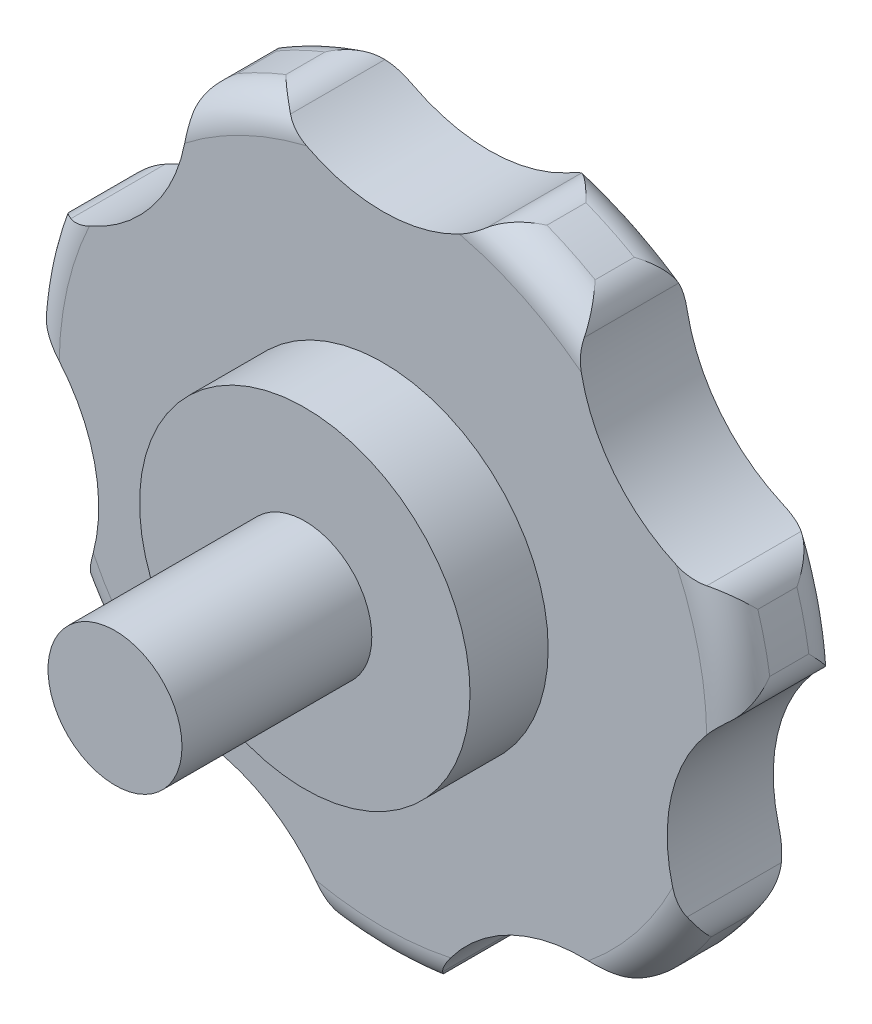
SolidWorks part; units mm, degrees
ref_plane "Front Plane" through (0, 0, 0) normal (0, 0, 1) x (1, 0, 0)
ref_plane "Top Plane" through (0, 0, 0) normal (0, 1, 0) x (1, 0, 0)
ref_plane "Right Plane" through (0, 0, 0) normal (1, 0, 0) x (0, 0, -1)
sketch "Sketch1" plane through (0, 0, 0) normal (0, 0, 1) x (1, 0, 0)
  circle A0 centre (0, 0) radius 16
  dimension "D1" = 32
extrude "Boss-Extrude1" add sketch "Sketch1" along normal blind 8.5
sketch "Sketch2" plane through (0, 0, 8.5) normal (0, 0, 1) x (1, 0, 0)
  circle A0 centre (0, 0) radius 7.4
  dimension "D1" = 14.8
extrude "Boss-Extrude2" add sketch "Sketch2" along normal blind 3.5
sketch "Sketch3" plane through (0, 0, 12) normal (0, 0, 1) x (1, 0, 0)
  circle A0 centre (0, 0) radius 3
  dimension "D1" = 6
extrude "Cut-Extrude1" cut sketch "Sketch3" against normal blind 3.5
sketch "Sketch4" plane through (0, 0, 0) normal (0, 1, 0) x (1, 0, 0)
  line L0 (-16, -3.75) -> (16, -3.75) construction
  line L1 (-16, 0) -> (-16, -8.5) construction
  line L2 (16, -8.5) -> (16, 0) construction
  line L3 (-8.5, 0) -> (-8.5, -8.5) construction
  line L4 (16, 0) -> (-16, 0) construction
  line L5 (-16, -8.5) -> (16, -8.5) construction
  line L6 (11, 0) -> (11, -8.5) construction
  line L7 (0, 0) -> (0, 2.9223)
  line L8 (0, 2.9223) -> (-18.6037, 2.9223)
  line L9 (-18.6037, 2.9223) -> (-18.6037, -3.75)
  line L10 (-18.6037, -3.75) -> (-8.5, -3.75)
  arc A0 (-8.5, -3.75) -> (0, 0) centre (0, -11.5083) cw
  point P16 (0, 0)
  dimension "D1" = 7.5
  dimension "D2" = 5
  dimension "D3" = 3.75
revolve "Cut-Revolve1" cut sketch "Sketch4" angle 360 about L7
sketch "Sketch5" plane through (0, 0, 3.75) normal (0, 0, -1) x (-1, 0, 0)
  arc A0 (-5, 15.1987) -> (5, 15.1987) centre (0, 20.6255) ccw
  circle A1 centre (0, 0) radius 16 construction
  arc A2 (8.7654, 13.3854) -> (15.0003, 5.5671) centre (16.1256, 12.8598) ccw
  arc A3 (15.9302, 1.4926) -> (13.705, -8.2567) centre (20.1083, -4.5896) ccw
  arc A4 (11.0993, -11.5241) -> (2.0896, -15.863) centre (8.9491, -18.5829) ccw
  arc A5 (-2.0896, -15.863) -> (-11.0993, -11.5241) centre (-8.9491, -18.5829) ccw
  arc A6 (-13.705, -8.2567) -> (-15.9302, 1.4926) centre (-20.1083, -4.5896) ccw
  arc A7 (-15.0003, 5.5671) -> (-8.7654, 13.3854) centre (-16.1256, 12.8598) ccw
  arc A8 (-15.0003, 5.5671) -> (-15.9302, 1.4926) centre (0, 0) ccw
  arc A9 (-5, 15.1987) -> (-8.7654, 13.3854) centre (0, 0) ccw
  arc A10 (8.7654, 13.3854) -> (5, 15.1987) centre (0, 0) ccw
  arc A11 (15.9302, 1.4926) -> (15.0003, 5.5671) centre (0, 0) ccw
  arc A12 (11.0993, -11.5241) -> (13.705, -8.2567) centre (0, 0) ccw
  arc A13 (-2.0896, -15.863) -> (2.0896, -15.863) centre (0, 0) ccw
  arc A14 (-13.705, -8.2567) -> (-11.0993, -11.5241) centre (0, 0) ccw
  circle A15 centre (0, 0) radius 17.9062
  point P28 (0, 0)
  dimension "D1" = 5
  dimension "D2" = 5
  dimension "D3" = 7
extrude "Cut-Extrude2" cut sketch "Sketch5" against normal through all
fillet "Fillet1" radius 1.5 28 edges at (12.5093, -9.9758, 8.5) (13.705, -8.2567, 6.125) (15.9302, 1.4926, 6.125) (12.5093, -9.9758, 3.75) (2.0896, -15.863, 6.125) (11.0993, -11.5241, 6.125) (15.5988, 3.5603, 8.5) (15.0003, 5.5671, 6.125) (8.7654, 13.3854, 6.125) (15.5988, 3.5603, 3.75) (6.9421, 14.4155, 3.75) (6.9421, 14.4155, 8.5) (5, 15.1987, 6.125) (-5, 15.1987, 6.125) (-6.9421, 14.4155, 8.5) (-8.7654, 13.3854, 6.125) (-15.0003, 5.5671, 6.125) (-6.9421, 14.4155, 3.75) (-15.5988, 3.5603, 8.5) (-15.9302, 1.4926, 6.125) (-13.705, -8.2567, 6.125) (-15.5988, 3.5603, 3.75) (-12.5093, -9.9758, 8.5) (-11.0993, -11.5241, 6.125) (-2.0896, -15.863, 6.125) (-12.5093, -9.9758, 3.75) (0, -16, 8.5) (0, -16, 3.75)
sketch "Sketch6" plane through (0, 0, 8.5) normal (0, 0, 1) x (1, 0, 0)
  circle A1 centre (0, 0) radius 3
  circle A2 centre (0, 0) radius 3
  dimension "D1" = 0
extrude "Boss-Extrude3" add sketch "Sketch6" along normal blind 12 separate body
